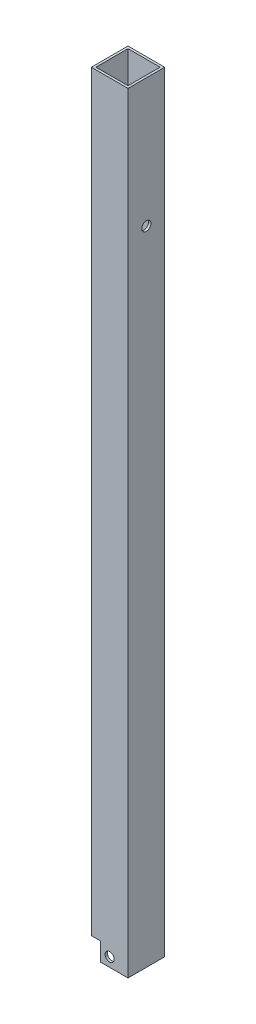
SolidWorks part; units mm, degrees
ref_plane "Front Plane" through (0, 0, 0) normal (0, 0, 1) x (1, 0, 0)
ref_plane "Top Plane" through (0, 0, 0) normal (0, 1, 0) x (1, 0, 0)
ref_plane "Right Plane" through (0, 0, 0) normal (1, 0, 0) x (0, 0, -1)
sketch "Sketch1" plane through (0, 0, 0) normal (0, 1, 0) x (1, 0, 0)
  line L1 (-12.7, -12.7) -> (12.7, -12.7)
  line L2 (-12.7, -12.7) -> (-12.7, 12.7)
  line L3 (-12.7, 12.7) -> (12.7, 12.7)
  line L4 (12.7, -12.7) -> (12.7, 12.7)
  line L5 (-12.7, -12.7) -> (12.7, 12.7) construction
  line L6 (-12.7, 12.7) -> (12.7, -12.7) construction
  line L7 (-11.1125, -11.1125) -> (11.1125, -11.1125)
  line L8 (-11.1125, -11.1125) -> (-11.1125, 11.1125)
  line L9 (-11.1125, 11.1125) -> (11.1125, 11.1125)
  line L10 (11.1125, -11.1125) -> (11.1125, 11.1125)
  line L11 (-11.1125, -11.1125) -> (11.1125, 11.1125) construction
  line L12 (-11.1125, 11.1125) -> (11.1125, -11.1125) construction
  point P0 (0, 0)
  point P6 (0, 0)
  dimension "D1" = 25.4
  dimension "D2" = 25.4
  dimension "D3" = 1.5875
  dimension "D4" = 1.5875
extrude "Boss-Extrude1" add sketch "Sketch1" along normal blind 533.4
sketch "Sketch2" plane through (0, 0, 12.7) normal (0, 0, 1) x (1, 0, 0)
  line L0 (-12.7, 0) -> (12.7, 0) construction
  line L3 (-6.35, 0) -> (-12.7, 0)
  line L4 (-6.35, 0) -> (-6.35, 12.7)
  line L6 (-6.35, 12.7) -> (-12.7, 12.7)
  line L7 (-12.7, 0) -> (-12.7, 12.7)
  line L8 (-12.7, 533.4) -> (-12.7, 0) construction
  line L9 (12.7, 533.4) -> (12.7, 0) construction
  dimension "D1" = 19.05
  dimension "D2" = 12.7
extrude "Cut-Extrude1" cut sketch "Sketch2" against normal blind 25.4
sketch "Sketch3" plane through (0, 0, 12.7) normal (0, 0, 1) x (1, 0, 0)
  line L0 (12.7, 533.4) -> (12.7, 0) construction
  line L1 (-6.35, 0) -> (12.7, 0) construction
  circle A0 centre (0, 6.35) radius 3.175
  dimension "D1" = 6.35
  dimension "D2" = 12.7
  dimension "D3" = 6.35
extrude "Cut-Extrude2" cut sketch "Sketch3" against normal blind 25.4
sketch "Sketch4" plane through (12.7, 0, 0) normal (1, 0, 0) x (0, 0, -1)
  line L0 (-12.7, 533.4) -> (12.7, 533.4) construction
  line L1 (-12.7, 533.4) -> (-12.7, 0) construction
  circle A0 centre (0, 444.5) radius 3.175
  dimension "D1" = 6.35
  dimension "D2" = 88.9
  dimension "D3" = 12.7
extrude "Cut-Extrude3" cut sketch "Sketch4" against normal blind 25.4
